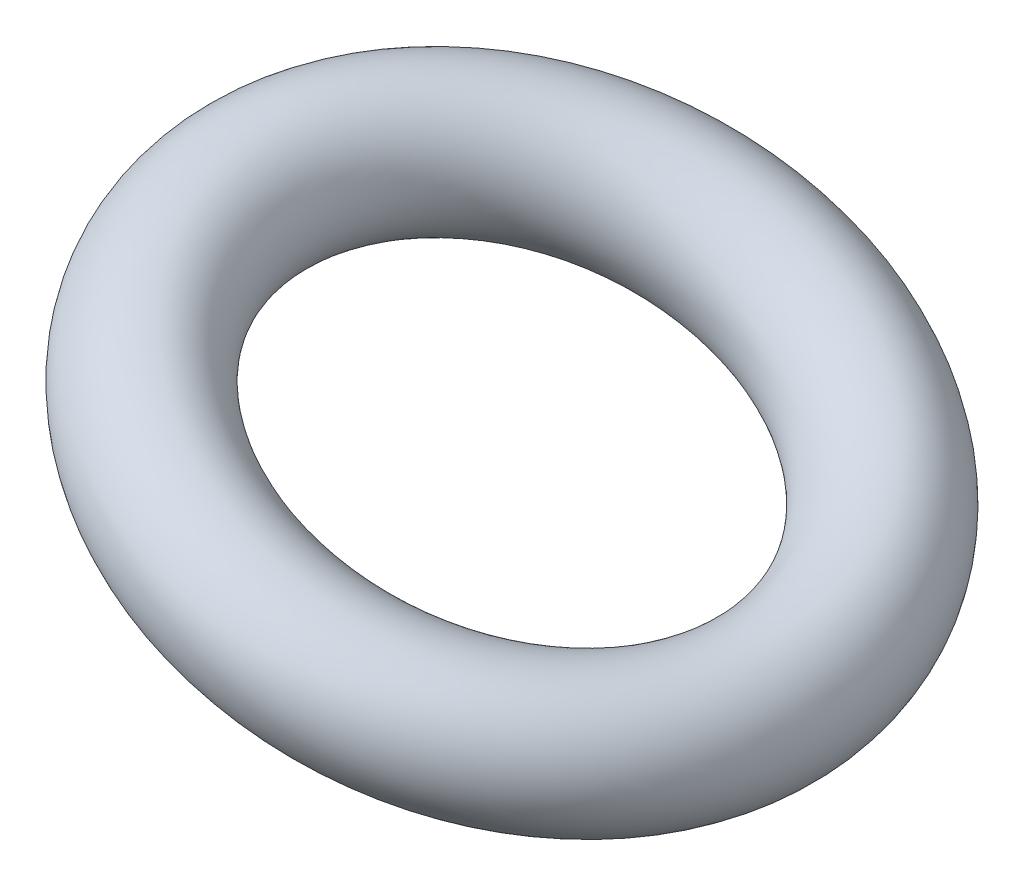
SolidWorks part; units mm, degrees
ref_plane "Front" through (0, 0, 0) normal (0, 0, 1) x (1, 0, 0)
ref_plane "Top" through (0, 0, 0) normal (0, 1, 0) x (1, 0, 0)
ref_plane "Right" through (0, 0, 0) normal (1, 0, 0) x (0, 0, -1)
sketch "Sketch1" plane through (0, 0, 0) normal (0, 0, 1) x (1, 0, 0)
  line L0 (-15.2999, 26.7676) -> (-31.5361, -15.861) construction
  circle A0 centre (-30.7734, 14.2367) radius 2.5
  dimension "D1" = 5
  dimension "D2" = 10
revolve "Revolve2" add sketch "Sketch1" angle 360 about L0
